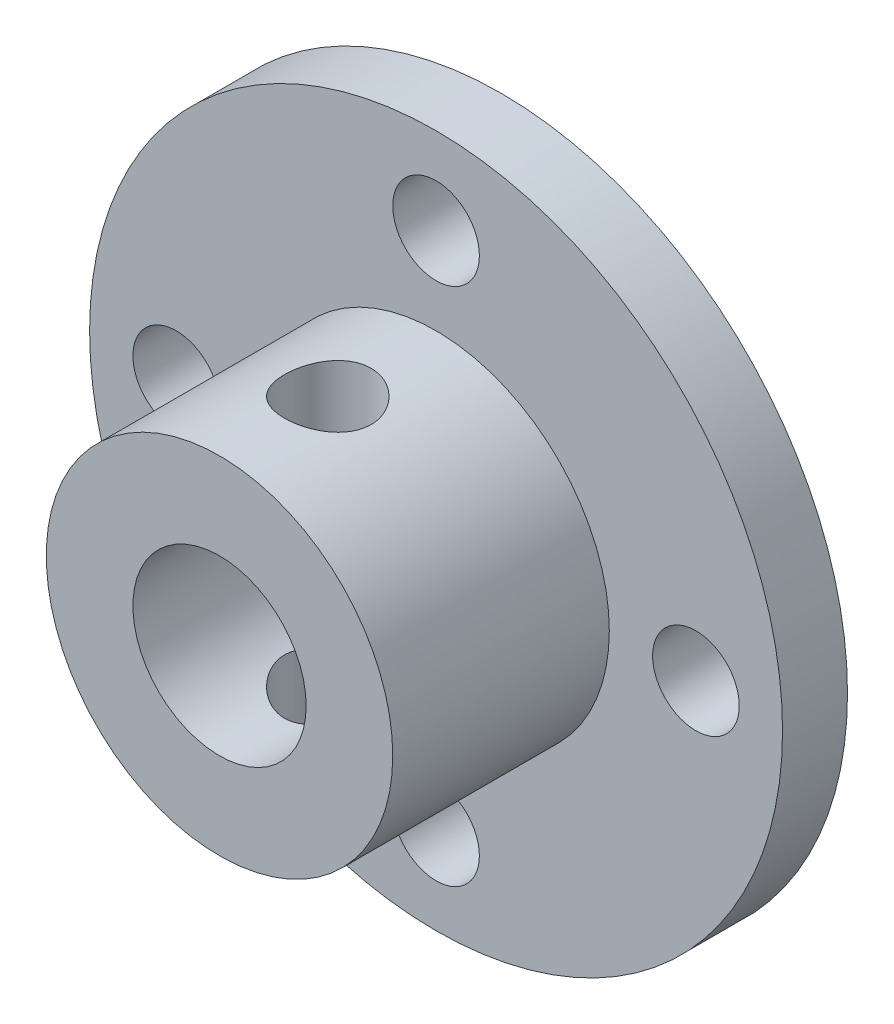
SolidWorks part; units mm, degrees
other "Markup1"
sketch "Sketch5" plane through (16, 16, 13) normal (0.1539, 0.7537, 0.639) x (0.5798, 0.4547, -0.6761)
ref_plane "Front Plane" through (0, 0, 0) normal (0, 0, 1) x (1, 0, 0)
ref_plane "Top Plane" through (0, 0, 0) normal (0, 1, 0) x (1, 0, 0)
ref_plane "Right Plane" through (0, 0, 0) normal (1, 0, 0) x (0, 0, -1)
sketch "Sketch1" plane through (0, 0, 0) normal (0, 0, 1) x (1, 0, 0)
  circle A0 centre (0, 0) radius 16
  dimension "D1" = 32
extrude "Boss-Extrude1" add sketch "Sketch1" along normal blind 3
sketch "Sketch2" plane through (0, 0, 3) normal (0, 0, 1) x (1, 0, 0)
  circle A0 centre (0, 0) radius 8
  circle A1 centre (0, 0) radius 4
  dimension "D1" = 8
  dimension "D2" = 16
extrude "Boss-Extrude2" add sketch "Sketch2" along normal blind 10
sketch "Sketch3" plane through (0, 0, 3) normal (0, 0, 1) x (1, 0, 0)
  line L0 (0, 0) -> (0, 12) construction
  line L1 (-12, 0) -> (0, 0) construction
  line L2 (12, 0) -> (0, 0) construction
  line L3 (0, 0) -> (0, -12) construction
  circle A0 centre (0, 12) radius 2
  circle A4 centre (12, 0) radius 2
  circle A5 centre (0, -12) radius 2
  circle A6 centre (-12, 0) radius 2
  dimension "D2" = 4
  dimension "D3" = 12
  dimension "D4" = 4
  dimension "D5" = 4
  dimension "D6" = 12
  dimension "D7" = 12
  dimension "D8" = 4
  dimension "D1" = 12
extrude "Cut-Extrude1" cut sketch "Sketch3" against normal through all
sketch "Sketch4" plane through (0, 0, 0) normal (0, 1, 0) x (1, 0, 0)
  line L0 (-8, -13) -> (8, -13) construction
  line L1 (8, -13) -> (8, -3) construction
  circle A0 centre (0, -8) radius 2
  dimension "D1" = 5
  dimension "D2" = 4
  dimension "D3" = 8
extrude "Cut-Extrude2" cut sketch "Sketch4" against normal through all both and the other way through all
sketch "Sketch6" plane through (0, 0, 3) normal (0, 0, 1) x (1, 0, 0)
  circle A1 centre (0, 0) radius 4
  circle A2 centre (0, 0) radius 4
  dimension "D1" = 0
extrude "Cut-Extrude3" cut sketch "Sketch6" against normal blind 10
